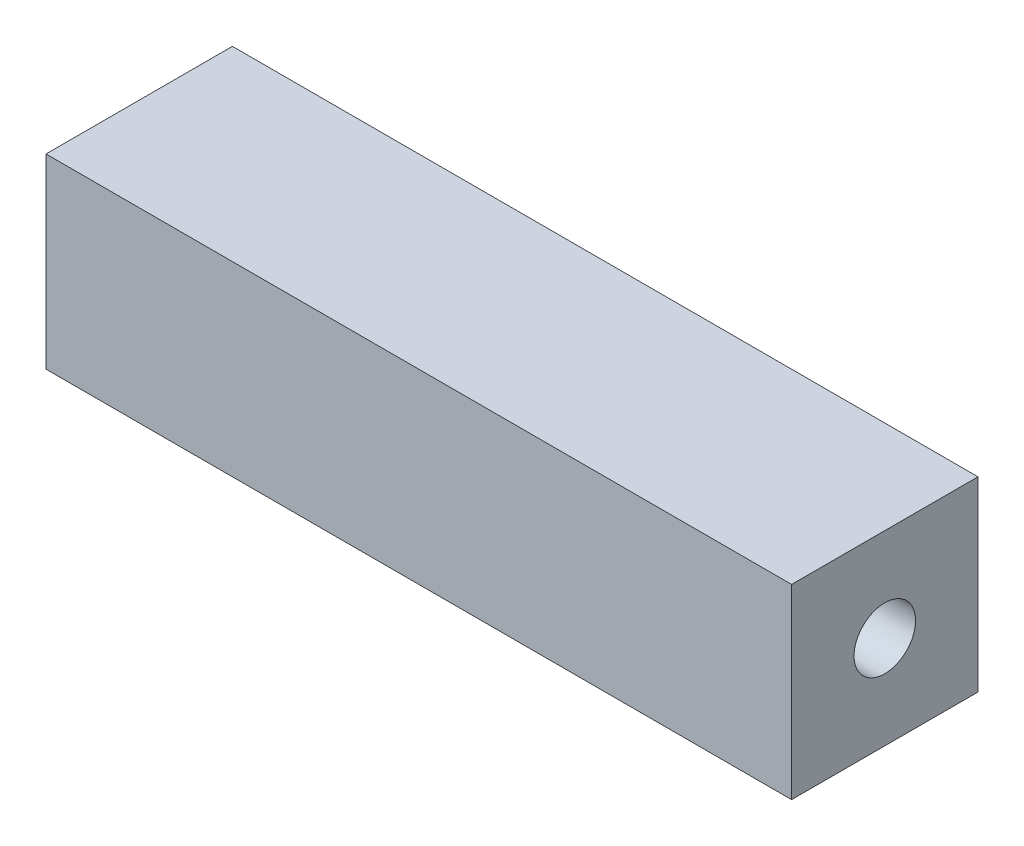
SolidWorks part; units mm, degrees
material "1060 Alloy"
ref_plane "Front Plane" through (0, 0, 0) normal (0, 0, 1) x (1, 0, 0)
ref_plane "Top Plane" through (0, 0, 0) normal (0, 1, 0) x (1, 0, 0)
ref_plane "Right Plane" through (0, 0, 0) normal (1, 0, 0) x (0, 0, -1)
sketch "Sketch1" plane through (0, 0, 0) normal (0, 1, 0) x (1, 0, 0)
  line L1 (-20, 5) -> (20, 5)
  line L2 (-20, 5) -> (-20, -5)
  line L3 (-20, -5) -> (20, -5)
  line L4 (20, 5) -> (20, -5)
  line L5 (-20, 5) -> (20, -5) construction
  line L6 (-20, -5) -> (20, 5) construction
  point P0 (0, 0)
  dimension "D1" = 40
  dimension "D2" = 10
extrude "Boss-Extrude1" add sketch "Sketch1" along normal blind 10
hole_wizard "M4x0.7 Tapped Hole1" positions "3DSketch1" profile "Sketch4" tap size "M4x0.7" standard "ANSI Metric"
sketch3d "3DSketch1"
  line L0 (20, 0, 5) -> (20, 10, -5) construction
  line L2 (-20, 0, 5) -> (-20, 10, -5) construction
  point P0 (-20, 5, 0)
  point P2 (20, 5, 0)
  point P14 (20, 5, 0)
  point P21 (-20, 5, 0)
sketch "Sketch4" plane through (-20, 5, 0) normal (0, 1, 0) x (0, 0, 1)
  line L0 (0, 0) -> (0, 16.9914)
  line L1 (0, 16.9914) -> (1.65, 16)
  line L2 (1.65, 16) -> (1.65, 0)
  line L5 (1.65, 0) -> (0, 0)
  line L10 (0, 16.9914) -> (-1.65, 16) construction
  line L11 (0, -6.35) -> (0, 107.95) construction
  dimension "Tap Drill Dia." = 3.3
  dimension "Tap Drill Depth" = 16
  dimension "Drill Angle" = 118
cosmetic thread "Hole Thread1"
cosmetic thread "Hole Thread2"
